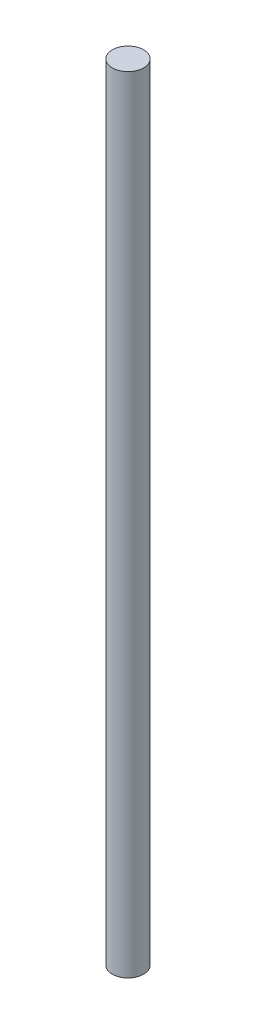
SolidWorks part; units mm, degrees
ref_plane "正面" through (0, 0, 0) normal (0, 0, 1) x (1, 0, 0)
ref_plane "平面" through (0, 0, 0) normal (0, 1, 0) x (1, 0, 0)
ref_plane "右側面" through (0, 0, 0) normal (1, 0, 0) x (0, 0, -1)
sketch "ｽｹｯﾁ1" plane through (0, 0, 0) normal (0, 1, 0) x (1, 0, 0)
  circle A0 centre (0, 0) radius 2
  dimension "D1" = 4
extrude "ﾎﾞｽ - 押し出し1" add sketch "ｽｹｯﾁ1" along normal blind 100
